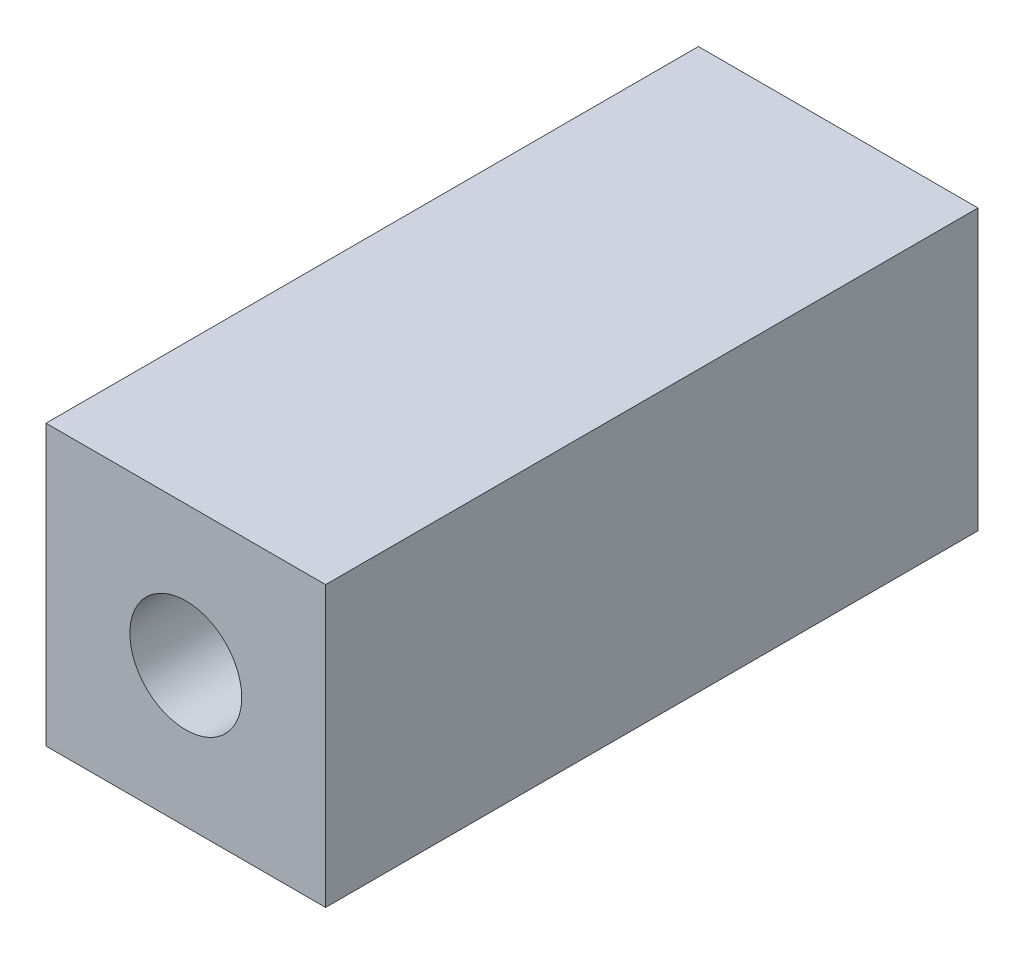
SolidWorks part; units mm, degrees
ref_plane "Front Plane" through (0, 0, 0) normal (0, 0, 1) x (1, 0, 0)
ref_plane "Top Plane" through (0, 0, 0) normal (0, 1, 0) x (1, 0, 0)
ref_plane "Right Plane" through (0, 0, 0) normal (1, 0, 0) x (0, 0, -1)
sketch "Sketch1" plane through (0, 0, 0) normal (0, 0, 1) x (1, 0, 0)
  line L1 (-15, 0) -> (-15, 15)
  line L2 (-15, 15) -> (15, 15)
  line L3 (15, 15) -> (15, -15)
  line L4 (15, -15) -> (-15, -15)
  line L5 (-15, -15) -> (-15, 0)
extrude "Boss-Extrude1" add sketch "Sketch1" along normal blind 70
sketch "Sketch2" plane through (0, 0, 70) normal (0, 0, 1) x (1, 0, 0)
  circle A0 centre (0, 0) radius 6
extrude "Cut-Extrude1" cut sketch "Sketch2" against normal through all
